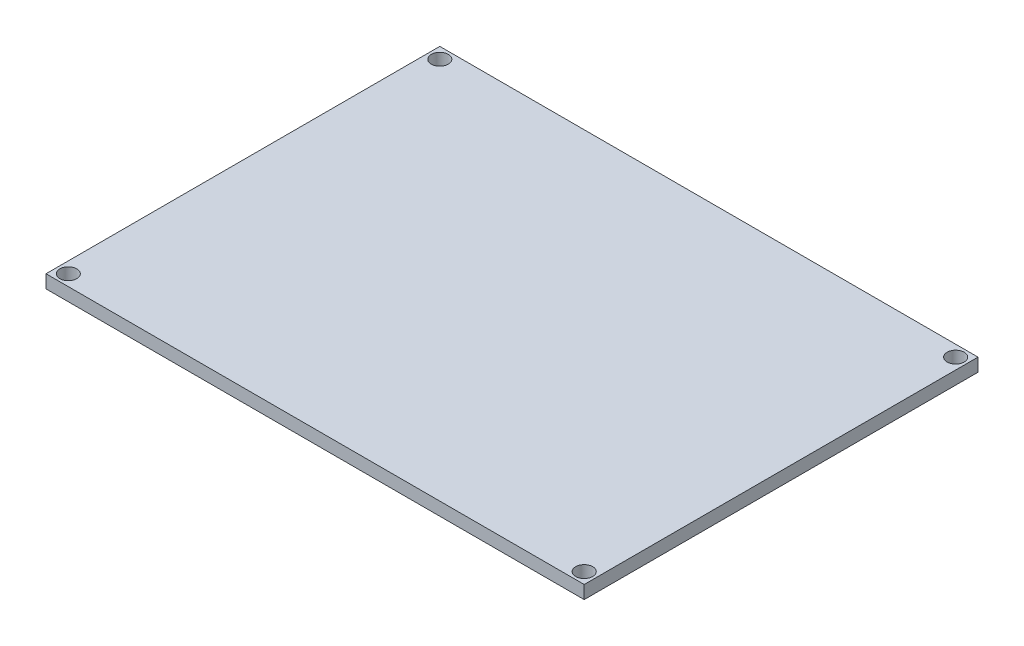
SolidWorks part; units mm, degrees
ref_plane "Front" through (0, 0, 0) normal (0, 0, 1) x (1, 0, 0)
ref_plane "Top" through (0, 0, 0) normal (0, 1, 0) x (1, 0, 0)
ref_plane "Right" through (0, 0, 0) normal (1, 0, 0) x (0, 0, -1)
sketch "Sketch1" plane through (0, 0, 0) normal (0, 1, 0) x (1, 0, 0)
  line L1 (0, 0) -> (82, 0)
  line L2 (0, 0) -> (0, -60)
  line L3 (0, -60) -> (82, -60)
  line L4 (82, 0) -> (82, -60)
  circle A0 centre (80.3, -58.3) radius 1.3
  circle A1 centre (80.3, -1.7) radius 1.3
  circle A2 centre (1.7, -1.7) radius 1.3
  circle A3 centre (1.7, -58.3) radius 1.3
  dimension "D3" = 2.6
  dimension "D6" = 2.6
  dimension "D9" = 2.6
  dimension "D12" = 2.6
  dimension "D1" = 82
  dimension "D2" = 60
  dimension "D4" = 1.7
  dimension "D5" = 1.7
  dimension "D7" = 1.7
  dimension "D8" = 1.7
  dimension "D10" = 1.7
  dimension "D11" = 1.7
  dimension "D13" = 1.7
  dimension "D14" = 1.7
extrude "Boss-Extrude1" add sketch "Sketch1" along normal blind 2
